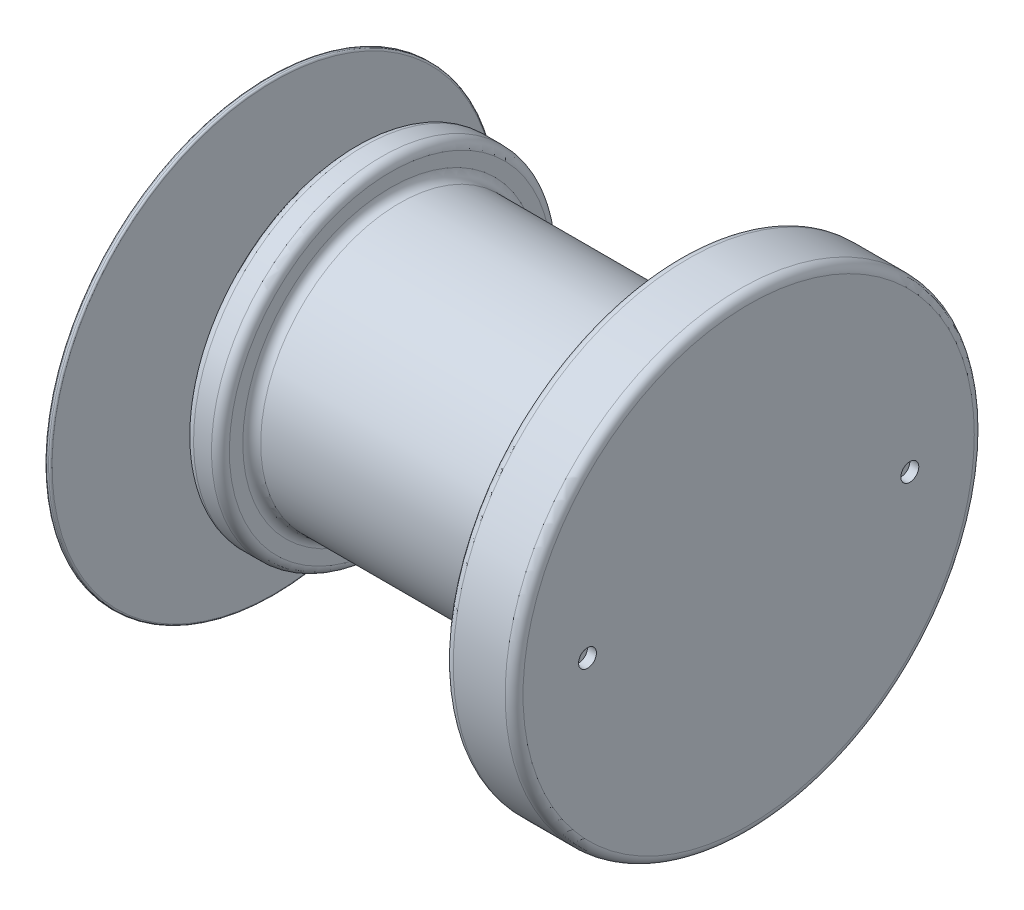
SolidWorks part; units mm, degrees
ref_plane "Front Plane" through (0, 0, 0) normal (0, 0, 1) x (1, 0, 0)
ref_plane "Top Plane" through (0, 0, 0) normal (0, 1, 0) x (1, 0, 0)
ref_plane "Right Plane" through (0, 0, 0) normal (1, 0, 0) x (0, 0, -1)
sketch "Sketch1" plane through (0, 0, 0) normal (1, 0, 0) x (0, -1, 0)
  circle A0 centre (0, 0) radius 131
  dimension "D1" = 262
extrude "Boss-Extrude1" add sketch "Sketch1" along normal blind 39
sketch "Sketch2" plane through (0, 0, 0) normal (-1, 0, 0) x (0, -1, 0)
  circle A0 centre (0, 0) radius 77.5
  dimension "D1" = 155
extrude "Boss-Extrude2" add sketch "Sketch2" along normal blind 181
sketch "Sketch3" plane through (-181, 0, 0) normal (-1, 0, 0) x (0, -1, 0)
  circle A0 centre (0, 0) radius 95
  dimension "D1" = 190
extrude "Boss-Extrude3" add sketch "Sketch3" against normal blind 20 separate body
sketch "Sketch4" plane through (-181, 0, 0) normal (-1, 0, 0) x (0, -1, 0)
  circle A0 centre (22.5, 0) radius 20
  dimension "D1" = 40
  dimension "D2" = 22.5
extrude "Boss-Extrude4" add sketch "Sketch4" along normal blind 45
sketch "Sketch5" plane through (-226, 0, 0) normal (-1, 0, 0) x (0, -1, 0)
  circle A0 centre (22.5, 0) radius 6
  dimension "D1" = 12
extrude "Boss-Extrude5" add sketch "Sketch5" along normal blind 22
sketch "Sketch6" plane through (-226, 0, 0) normal (-1, 0, 0) x (0, -1, 0)
  circle A0 centre (22.5, 0) radius 125
  dimension "D1" = 250
extrude "Boss-Extrude6" add sketch "Sketch6" along normal blind 3
sketch "Sketch7" plane through (-248, 0, 0) normal (-1, 0, 0) x (0, -1, 0)
  circle A0 centre (22.5, 0) radius 14
  dimension "D1" = 28
extrude "Boss-Extrude7" add sketch "Sketch7" against normal blind 10
sketch "Sketch8" plane through (39, 0, 0) normal (1, 0, 0) x (0, -1, 0)
  circle A0 centre (0, 90) radius 5
  circle A1 centre (0, -90) radius 5
  dimension "D1" = 10
  dimension "D2" = 90
  dimension "D3" = 90
extrude "Cut-Extrude1" cut sketch "Sketch8" against normal blind 5
fillet "Fillet1" radius 1 2 edges at (-238, -36.5, 0) (-248, -36.5, 0)
fillet "Fillet2" radius 1 2 edges at (-229, -147.5, 0) (-226, -147.5, 0)
fillet "Fillet3" radius 5 6 edges at (39, 0, -131) (0, 0, -131) (-161, -77.5, 0) (0, 0, -77.5) (-161, -95, 0) (-181, -95, 0)
